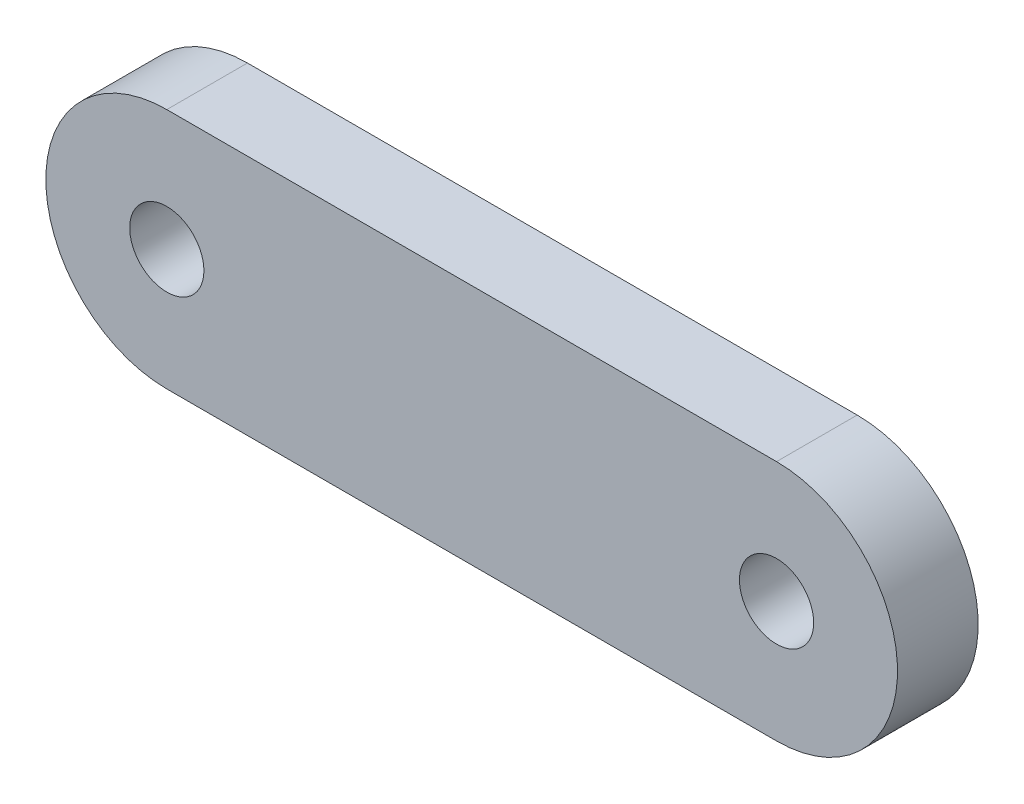
SolidWorks part; units mm, degrees
ref_plane "前视基准面" through (0, 0, 0) normal (0, 0, 1) x (1, 0, 0)
ref_plane "上视基准面" through (0, 0, 0) normal (0, 1, 0) x (1, 0, 0)
ref_plane "右视基准面" through (0, 0, 0) normal (1, 0, 0) x (0, 0, -1)
other "Configuration Table"
sketch "草图1" plane through (0, 0, 0) normal (0, 0, 1) x (1, 0, 0)
  line L1 (-18.9, 7.5) -> (18.9, 7.5)
  line L3 (-18.9, -7.5) -> (18.9, -7.5)
  line L5 (-18.9, 7.5) -> (18.9, -7.5) construction
  line L6 (-18.9, -7.5) -> (18.9, 7.5) construction
  arc A0 (-18.9, 7.5) -> (-18.9, -7.5) centre (-18.9, 0) ccw
  arc A1 (18.9, 7.5) -> (18.9, -7.5) centre (18.9, 0) cw
  circle A2 centre (-18.9, 0) radius 2.3
  circle A3 centre (18.9, 0) radius 2.3
  point P0 (0, 0)
  dimension "D1" = 4.6
  dimension "D2" = 4.6
  dimension "D4" = 15
  dimension "D3" = 37.8
extrude "凸台-拉伸1" add sketch "草图1" along normal blind 5
equation "\"fi\"=4.6"
equation "\"D1@草图1\"=\"fi\""
equation "\"D2@草图1\"=\"fi\""
equation "\"b0\"= 75.6'ground"
equation "\"width\"=15"
equation "\"D4@草图1\"=\"width\""
equation "\"depth\"=5"
equation "\"D1@凸台-拉伸1\"=\"depth\""
equation "\"b1\"= \"b0\" *1.4/ 2'rocker"
equation "\"b2\"= \"b0\"'coupler"
equation "\"b3\"= \"b0\" / 2'coupler"
equation "\"b4\"= \"b0\" *2'leg"
equation "\"angle\"= 40*pi/180'ground水平夹角"
equation "\"D3@草图1\"=\"b3\""
